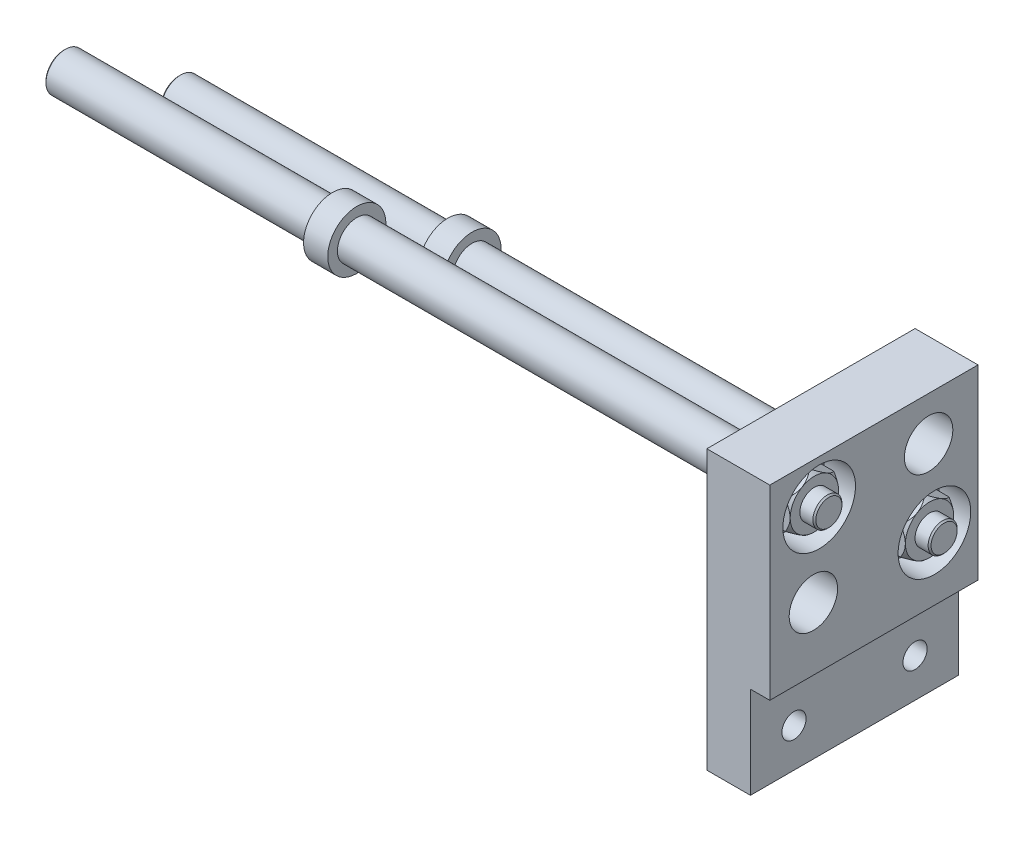
SolidWorks part; units mm, degrees
ref_plane "Front" through (0, 0, 0) normal (0, 0, 1) x (1, 0, 0)
ref_plane "Top" through (0, 0, 0) normal (0, 1, 0) x (1, 0, 0)
ref_plane "Right" through (0, 0, 0) normal (1, 0, 0) x (0, 0, -1)
sketch "Sketch1" plane through (0, 0, 0) normal (0, 0, 1) x (1, 0, 0)
  line L1 (0, 9) -> (13, 9)
  line L2 (0, 9) -> (0, -48.5)
  line L3 (0, -48.5) -> (13, -48.5)
  line L4 (13, 9) -> (13, -48.5)
  dimension "D1" = 13
  dimension "D2" = 57.5
  dimension "D3" = 9
extrude "Boss-Extrude1" add sketch "Sketch1" along normal blind 10.2 and the other way blind 32.8
ref_plane "Piston Plane" through (-87.5, 0, 0) normal (1, 0, 0) x (0, 0, -1)
sketch "Sketch3" plane through (0, 0, 0) normal (0, 0, 1) x (1, 0, 0)
  line L1 (13, -48.5) -> (9, -48.5)
  line L2 (13, -48.5) -> (13, -29.5)
  line L3 (13, -29.5) -> (9, -29.5)
  line L4 (9, -48.5) -> (9, -29.5)
  dimension "D1" = 4
  dimension "D2" = 19
extrude "Cut-Extrude1" cut sketch "Sketch3" against normal through all and the other way through all
sketch "Sketch4" plane through (13, 0, 0) normal (1, 0, 0) x (0, 0, -1)
  line L0 (11.3, 9) -> (11.3, -29.5) construction
  line L1 (32.8, 9) -> (-10.2, 9) construction
  line L2 (32.8, -29.5) -> (-10.2, -29.5) construction
  line L3 (23.8, 9) -> (23.8, -29.5) construction
  circle A0 centre (0, 0) radius 7.5
  circle A1 centre (23.8, -16.5) radius 7.5
  dimension "D1" = 15
  dimension "D4" = 15
  dimension "D3" = 16.5
  dimension "D2" = 12.5
extrude "Cut-Extrude2" cut sketch "Sketch4" against normal blind 6.5
sketch "Sketch5" plane through (6.5, 0, 0) normal (1, 0, 0) x (0, 0, -1)
  line L1 (0, 5.7735) -> (-5, 2.8868)
  line L2 (-5, 2.8868) -> (-5, -2.8868)
  line L3 (-5, -2.8868) -> (0, -5.7735)
  line L4 (0, -5.7735) -> (5, -2.8868)
  line L5 (5, -2.8868) -> (5, 2.8868)
  line L6 (5, 2.8868) -> (0, 5.7735)
  line L7 (23.8, -10.7265) -> (18.8, -13.6132)
  line L8 (18.8, -13.6132) -> (18.8, -19.3868)
  line L9 (18.8, -19.3868) -> (23.8, -22.2735)
  line L10 (23.8, -22.2735) -> (28.8, -19.3868)
  line L11 (28.8, -19.3868) -> (28.8, -13.6132)
  line L12 (28.8, -13.6132) -> (23.8, -10.7265)
  circle A0 centre (0, 0) radius 5 construction
  circle A1 centre (23.8, -16.5) radius 5 construction
  dimension "D1" = 10
  dimension "D2" = 10
extrude "Boss-Extrude2" add sketch "Sketch5" along normal blind 5.5
ref_plane "Plane1" through (0, 0, 0) normal (0, 0, -1) x (-1, 0, 0)
sketch "Sketch6" plane through (0, 0, 0) normal (0, 0, -1) x (-1, 0, 0)
  line L0 (-12, 5.7735) -> (-12, 4.9922)
  line L1 (-12, 4.9922) -> (-11, 5.7735)
  line L2 (-12, 5.7735) -> (-6.5, 5.7735) construction
  line L3 (-11, 5.7735) -> (-12, 5.7735)
  line L4 (-12, -2.8868) -> (-12, 2.8868) construction
  line L5 (-12, -2.8868) -> (-12, 2.8868) construction
  line L6 (-6.5, -2.8868) -> (-6.5, 2.8868) construction
  line L7 (-6.5, -2.8868) -> (-6.5, 2.8868) construction
  line L8 (-6.5, 0) -> (-12, 0) construction
  dimension "D1" = 1
  dimension "D2" = 52
revolve "Cut-Revolve1" cut sketch "Sketch6" angle 360 about L8
ref_plane "Plane2" through (0, 0, -23.8) normal (0, 0, -1) x (-1, 0, 0)
sketch "Sketch7" plane through (0, 0, -23.8) normal (0, 0, -1) x (-1, 0, 0)
  line L0 (-11, -10.7265) -> (-12, -10.7265)
  line L1 (-12, -10.7265) -> (-6.5, -10.7265) construction
  line L2 (-12, -10.7265) -> (-12, -11.5078)
  line L3 (-12, -11.5078) -> (-11, -10.7265)
  line L4 (-12, -19.3868) -> (-12, -13.6132) construction
  line L5 (-12, -19.3868) -> (-12, -13.6132) construction
  line L6 (-6.5, -19.3868) -> (-6.5, -13.6132) construction
  line L7 (-6.5, -19.3868) -> (-6.5, -13.6132) construction
  line L8 (-6.5, -16.5) -> (-9.1349, -16.5) construction
  dimension "D1" = 1
  dimension "D2" = 52
revolve "Cut-Revolve2" cut sketch "Sketch7" angle 360 about L8
sketch "Sketch8" plane through (12, 0, 0) normal (1, 0, 0) x (0, 0, -1)
  circle A0 centre (0, 0) radius 3
  circle A1 centre (23.8, -16.5) radius 3
  dimension "D1" = 6
  dimension "D2" = 6
extrude "Boss-Extrude3" add sketch "Sketch8" along normal blind 3
chamfer "Chamfer1" distance 0.3 angle 45 2 edges at (15, -13.5, -23.8) (15, 3, 0)
sketch "Sketch10" plane through (0, 0, 0) normal (1, 0, 0) x (0, 0, -1)
  line L0 (23.8, -16.5) -> (-1.2, -16.5) construction
  circle A0 centre (22.6, 0) radius 5
  circle A1 centre (-1.2, -16.5) radius 5
  dimension "D3" = 10
  dimension "D4" = 10
  dimension "D1" = 22.6
  dimension "D2" = 25
extrude "Cut-Extrude3" cut sketch "Sketch10" along normal through all
sketch "Sketch9" plane through (0, 0, 0) normal (1, 0, 0) x (0, 0, -1)
  circle A0 centre (23.8, -16.5) radius 3 construction
  circle A1 centre (0, 0) radius 3 construction
  circle A2 centre (23.8, -16.5) radius 3 construction
  circle A3 centre (0, 0) radius 3 construction
  circle A4 centre (23.8, -16.5) radius 4
  circle A5 centre (0, 0) radius 4
  dimension "D1" = 8
  dimension "D2" = 8
extrude "Boss-Extrude4" add sketch "Sketch9" against normal blind 143
chamfer "Chamfer2" distance 0.3 angle 45 2 edges at (-143, 0, -4) (-143, -16.5, -27.8)
sketch "Sketch11" plane through (0, 0, 0) normal (1, 0, 0) x (0, 0, -1)
  line L0 (11.3, -40.5) -> (11.3, -48.5) construction
  line L2 (32.8, -48.5) -> (-10.2, -48.5) construction
  line L3 (-1.2, -40.5) -> (23.8, -40.5) construction
  circle A0 centre (-1.2, -40.5) radius 2.5
  circle A1 centre (23.8, -40.5) radius 2.5
  dimension "D1" = 5
  dimension "D2" = 25
  dimension "D3" = 8
extrude "Cut-Extrude4" cut sketch "Sketch11" along normal through all
sketch "Sketch12" plane through (-87.5, 0, 0) normal (1, 0, 0) x (0, 0, -1)
  circle A0 centre (0, 0) radius 6
  circle A1 centre (23.8, -16.5) radius 6
  dimension "D1" = 12
  dimension "D2" = 12
extrude "Boss-Extrude5" add sketch "Sketch12" along normal blind 5
